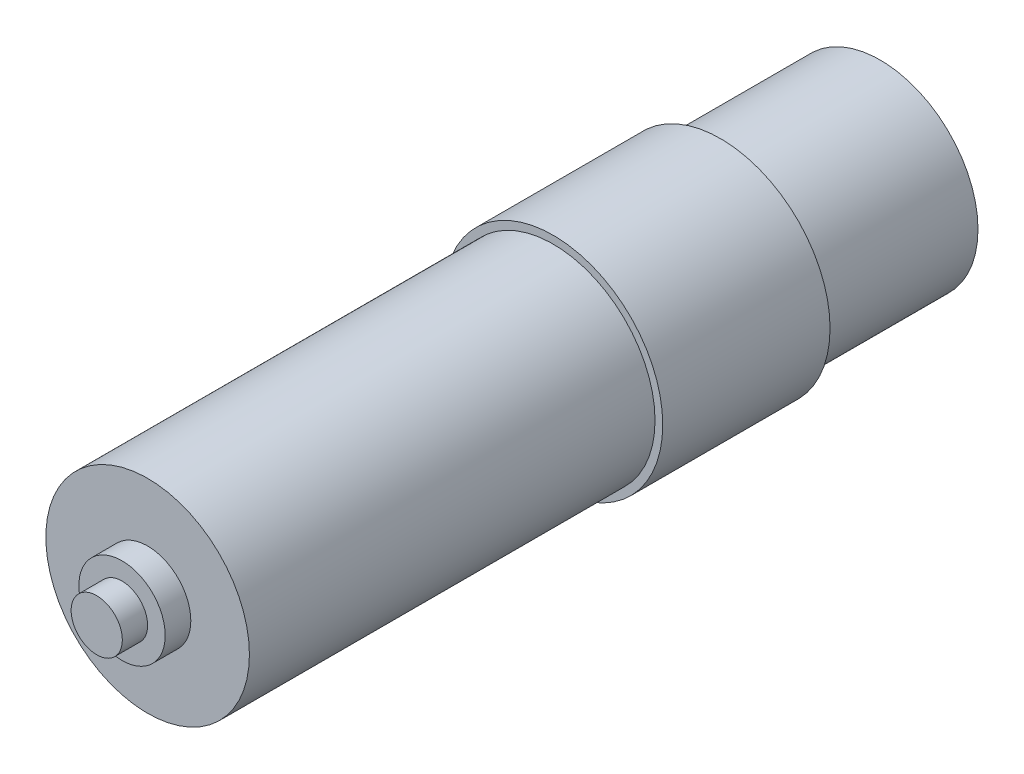
SolidWorks part; units mm, degrees
ref_plane "Front Plane" through (0, 0, 0) normal (0, 0, 1) x (1, 0, 0)
ref_plane "Top Plane" through (0, 0, 0) normal (0, 1, 0) x (1, 0, 0)
ref_plane "Right Plane" through (0, 0, 0) normal (1, 0, 0) x (0, 0, -1)
sketch "Sketch1" plane through (0, 0, 0) normal (1, 0, 0) x (0, 0, -1)
  line L0 (0, 0) -> (-127, 0)
  line L1 (0, 0) -> (0, 15.85)
  line L2 (0, 15.85) -> (-25.88, 15.85)
  line L3 (-25.88, 15.85) -> (-25.88, 17.75)
  line L4 (-25.88, 17.75) -> (-53, 17.75)
  line L5 (-53, 17.75) -> (-53, 16.5)
  line L6 (-53, 16.5) -> (-118.75, 16.5)
  line L7 (-118.75, 16.5) -> (-118.75, 7)
  line L8 (-118.75, 7) -> (-122.9, 7)
  line L9 (-122.9, 7) -> (-122.9, 4.15)
  line L10 (-122.9, 4.15) -> (-127, 4.15)
  line L11 (-127, 4.15) -> (-127, 0)
  line L12 (0, 0) -> (30, 0) construction
  dimension "D1" = 127
  dimension "D2" = 30
  dimension "D3" = 31.7
  dimension "D4" = 35.5
  dimension "D5" = 33
  dimension "D6" = 14
  dimension "D7" = 8.3
  dimension "D8" = 25.88
  dimension "D9" = 53
  dimension "D10" = 118.75
  dimension "D11" = 4.15
revolve "Revolve1" add sketch "Sketch1" angle 360 about L12
